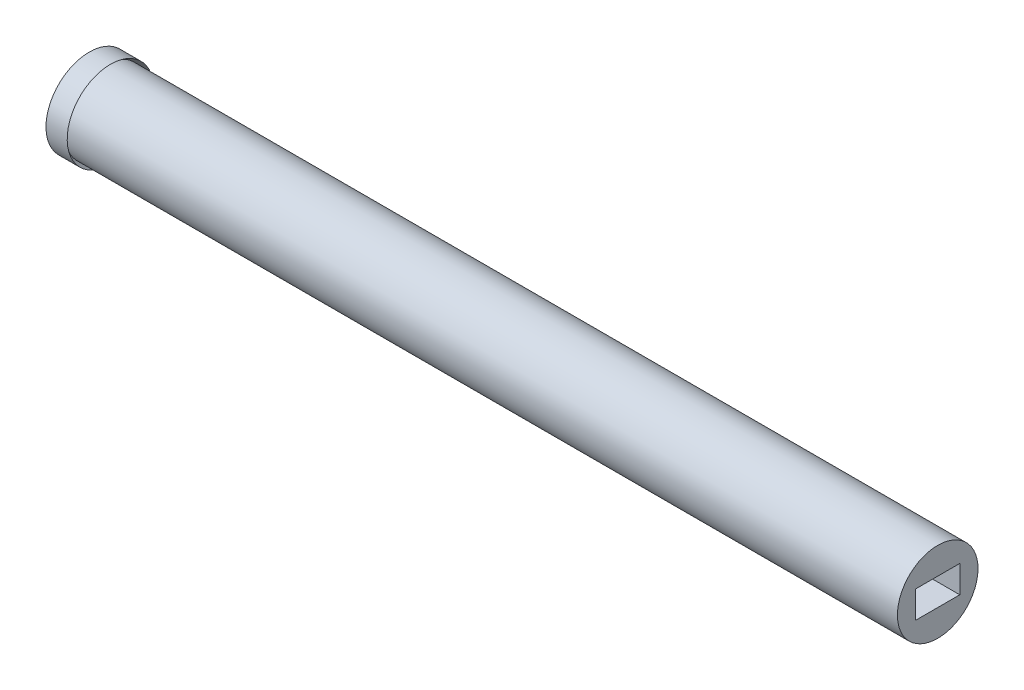
SolidWorks part; units mm, degrees
ref_plane "Front Plane" through (0, 0, 0) normal (0, 0, 1) x (1, 0, 0)
ref_plane "Top Plane" through (0, 0, 0) normal (0, 1, 0) x (1, 0, 0)
ref_plane "Right Plane" through (0, 0, 0) normal (1, 0, 0) x (0, 0, -1)
sketch "Sketch1" plane through (0, 0, 0) normal (0, 0, 1) x (1, 0, 0)
  line L0 (0, 0) -> (2.5, 0)
  line L1 (2.5, 0) -> (1.8938, 0.35)
  line L2 (1.8938, 0.35) -> (100, 0.35)
  line L3 (100, 0.35) -> (100, 5.1)
  line L4 (100, 5.1) -> (0, 5.1)
  line L5 (0, 5.1) -> (0, 0)
  dimension "D1" = 100
  dimension "D2" = 4.75
  dimension "D3" = 2.5
  dimension "D4" = 0.7
  dimension "D5" = 5.1
revolve "Revolve2" add sketch "Sketch1" angle 360 about L4
sketch "Sketch4" plane through (100, 0, 0) normal (1, 0, 0) x (0, 0, -1)
  line L0 (0, 10.2) -> (0, 0) construction
  line L1 (-2.6, 6.7) -> (2.6, 6.7)
  line L2 (-2.6, 6.7) -> (-2.6, 3.5)
  line L3 (-2.6, 3.5) -> (2.6, 3.5)
  line L4 (2.6, 6.7) -> (2.6, 3.5)
  line L5 (-5.1, 5.1) -> (5.1, 5.1) construction
  circle A0 centre (0, 5.1) radius 5.1 construction
  point P12 (0, 5.1)
  dimension "D1" = 1.6
  dimension "D2" = 5.2
  dimension "D3" = 3.2
  dimension "D4" = 2.6
extrude "Cut-Extrude1" cut sketch "Sketch4" against normal blind 4.3
